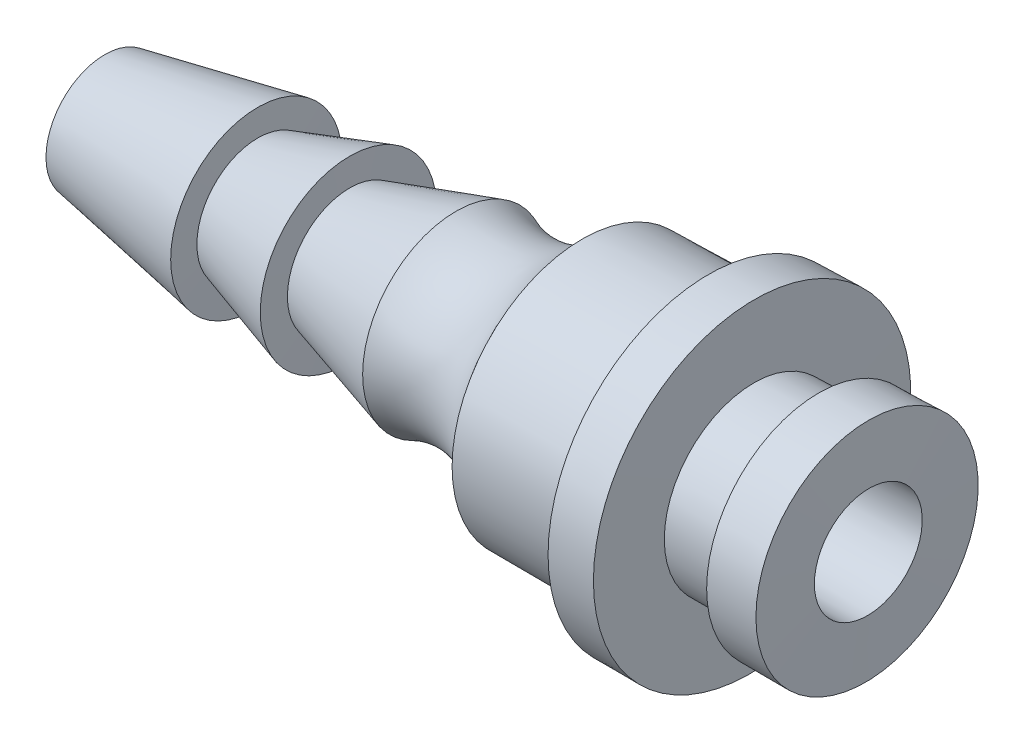
SolidWorks part; units mm, degrees
ref_plane "Front Plane" through (0, 0, 0) normal (0, 0, 1) x (1, 0, 0)
ref_plane "Top Plane" through (0, 0, 0) normal (0, 1, 0) x (1, 0, 0)
ref_plane "Right Plane" through (0, 0, 0) normal (1, 0, 0) x (0, 0, -1)
sketch "Sketch1" plane through (0, 0, 0) normal (0, 1, 0) x (1, 0, 0)
  line L0 (-11.4935, -0.9609) -> (1.4065, -0.9609)
  line L1 (-11.4935, -0.1109) -> (22.6543, 0.3696) construction
  line L2 (-11.4935, -1.6709) -> (-11.4935, -0.9609)
  line L3 (-11.4935, -1.6709) -> (-7.4995, -2.3599)
  line L4 (-7.4995, -2.3599) -> (-7.4935, -1.6709)
  line L5 (-7.4935, -1.6709) -> (-5.0935, -2.3911)
  line L6 (-5.0935, -2.3911) -> (-5.0935, -1.6709)
  line L7 (-5.0935, -1.6709) -> (-2.3135, -2.457)
  line L8 (-11.4935, -0.1109) -> (-11.4935, -4.1596) construction
  line L9 (-0.5438, -2.207) -> (-2.982, -2.207) construction
  line L10 (0.9865, -3.3856) -> (4.2865, -3.3856)
  line L11 (4.2865, -3.3856) -> (4.2844, -4.1393)
  line L12 (4.2844, -4.1393) -> (5.4865, -4.1393)
  line L13 (5.4865, -4.1393) -> (5.474, -2.2474)
  line L14 (5.474, -2.2474) -> (7.174, -2.2474)
  line L15 (7.174, -2.2474) -> (7.1675, -2.8186)
  line L16 (7.1675, -2.8186) -> (8.474, -2.8186)
  line L17 (8.474, -2.8186) -> (8.485, -1.2799)
  line L18 (8.485, -1.2799) -> (1.8262, -1.2799)
  line L19 (1.4065, -0.9609) -> (1.8262, -1.2799)
  arc A0 (-2.3135, -2.457) -> (0.9865, -3.3856) centre (-1.1981, -4.821) cw
  point P0 (-11.4935, -0.9609)
  point P5 (-11.4935, -1.6709)
  point P6 (-11.4935, -1.6709)
  point P7 (-11.4935, -0.1109)
  point P9 (-7.4935, -1.6709)
  point P10 (-7.4995, -2.3599)
  point P11 (-5.0935, -1.6709)
  point P12 (-5.0935, -2.3911)
  point P13 (-2.3135, -1.6709)
  point P14 (-2.3135, -2.457)
  point P15 (0.9865, -3.3856)
  point P20 (0.9865, -3.3856)
  point P23 (0.9865, -1.6709)
  point P24 (-2.3135, -1.6709)
  point P25 (0.9865, -1.6709)
  point P26 (-0.5438, -2.207)
  point P31 (4.2865, -1.6709)
  point P32 (4.2844, -4.1393)
  point P33 (4.2865, -3.3856)
  point P35 (5.4865, -4.1393)
  point P37 (5.4865, -1.6709)
  point P38 (5.474, -2.2474)
  point P41 (8.474, -1.6709)
  point P43 (7.174, -1.6709)
  point P44 (7.1675, -2.8186)
  point P45 (7.1675, -2.8186)
  point P46 (8.485, -1.2799)
  dimension "D1" = 0.85
  dimension "D2" = 1.56
  dimension "D3" = 4
  dimension "D4" = 2.305
  dimension "D5" = 2.4
  dimension "D6" = 2.25
  dimension "D7" = 3.3
  dimension "D8" = 2.37
  dimension "D9" = 2.475
  dimension "D10" = 2.78
  dimension "D11" = 3.45
  dimension "D12" = 3.3
  dimension "D13" = 4.25
  dimension "D14" = 1.2
  dimension "D15" = 2.375
  dimension "D16" = 1.7
  dimension "D17" = 1.3
  dimension "D18" = 2.97
  dimension "D19" = 1.45
revolve "Revolve1" add sketch "Sketch1" angle 360 about L1
